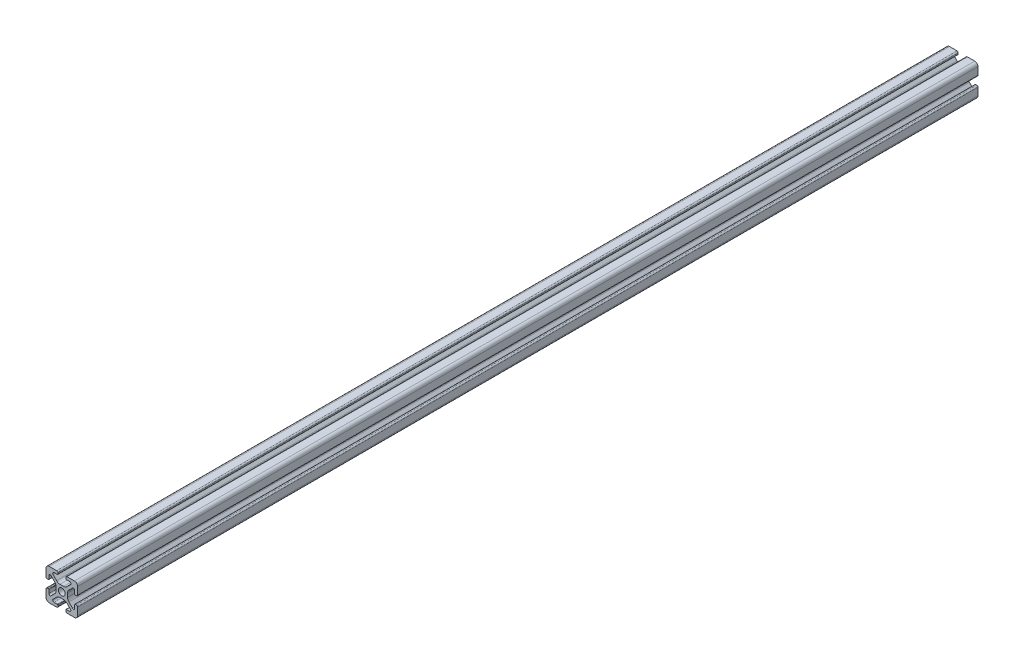
SolidWorks part; units mm, degrees
ref_plane "Front Plane" through (0, 0, 0) normal (0, 0, 1) x (1, 0, 0)
ref_plane "Top Plane" through (0, 0, 0) normal (0, 1, 0) x (1, 0, 0)
ref_plane "Right Plane" through (0, 0, 0) normal (1, 0, 0) x (0, 0, -1)
sketch "Sketch1" plane through (0, 0, 0) normal (0, 0, 1) x (1, 0, 0)
  line L2 (-9.9949, 7.9883) -> (-9.9949, 3.2893)
  line L3 (-7.9883, 9.9949) -> (-3.2893, 9.9949)
  line L4 (-2.5019, 9.2075) -> (-2.5019, 8.4963)
  line L5 (-2.8067, 8.1915) -> (-4.9149, 8.1915)
  line L6 (-5.5076, 6.7606) -> (-3.2528, 4.5058)
  line L7 (-6.7606, 5.5076) -> (-4.5058, 3.2528)
  line L8 (-8.1915, 4.9149) -> (-8.1915, 2.8067)
  line L9 (-8.4963, 2.5019) -> (-9.2075, 2.5019)
  line L11 (-1.1334, 3.6279) -> (1.1334, 3.6279)
  line L12 (-3.6279, 1.1334) -> (-3.6279, -1.1334)
  line L13 (8.4963, 2.5019) -> (9.2075, 2.5019)
  line L14 (8.1915, 4.9149) -> (8.1915, 2.8067)
  line L15 (9.9949, 7.9883) -> (9.9949, 3.2893)
  line L16 (7.9883, 9.9949) -> (3.2893, 9.9949)
  line L17 (2.5019, 9.2075) -> (2.5019, 8.4963)
  line L18 (2.8067, 8.1915) -> (4.9149, 8.1915)
  line L19 (3.6279, 1.1334) -> (3.6279, -1.1334)
  line L20 (5.5076, 6.7606) -> (3.2528, 4.5058)
  line L21 (6.7606, 5.5076) -> (4.5058, 3.2528)
  line L22 (-8.4963, -2.5019) -> (-9.2075, -2.5019)
  line L23 (-8.1915, -4.9149) -> (-8.1915, -2.8067)
  line L24 (-6.7606, -5.5076) -> (-4.5058, -3.2528)
  line L25 (-5.5076, -6.7606) -> (-3.2528, -4.5058)
  line L26 (-2.8067, -8.1915) -> (-4.9149, -8.1915)
  line L27 (-2.5019, -9.2075) -> (-2.5019, -8.4963)
  line L28 (-7.9883, -9.9949) -> (-3.2893, -9.9949)
  line L29 (-9.9949, -7.9883) -> (-9.9949, -3.2893)
  line L30 (9.9949, -7.9883) -> (9.9949, -3.2893)
  line L31 (7.9883, -9.9949) -> (3.2893, -9.9949)
  line L32 (2.5019, -9.2075) -> (2.5019, -8.4963)
  line L33 (2.8067, -8.1915) -> (4.9149, -8.1915)
  line L34 (5.5076, -6.7606) -> (3.2528, -4.5058)
  line L35 (6.7606, -5.5076) -> (4.5058, -3.2528)
  line L36 (8.1915, -4.9149) -> (8.1915, -2.8067)
  line L37 (8.4963, -2.5019) -> (9.2075, -2.5019)
  line L38 (-1.1334, -3.6279) -> (1.1334, -3.6279)
  circle A0 centre (0, 0) radius 2.1463
  arc A1 (-9.9949, 7.9883) -> (-7.9883, 9.9949) centre (-7.9883, 7.9883) cw
  arc A2 (-6.7606, 5.5076) -> (-8.1915, 4.9149) centre (-7.3533, 4.9149) ccw
  arc A3 (-4.9149, 8.1915) -> (-5.5076, 6.7606) centre (-4.9149, 7.3533) ccw
  arc A4 (-3.2893, 9.9949) -> (-2.5019, 9.2075) centre (-3.2893, 9.2075) cw
  arc A5 (-9.9949, 3.2893) -> (-9.2075, 2.5019) centre (-9.2075, 3.2893) ccw
  arc A6 (-8.1915, 2.8067) -> (-8.4963, 2.5019) centre (-8.4963, 2.8067) cw
  arc A7 (-2.5019, 8.4963) -> (-2.8067, 8.1915) centre (-2.8067, 8.4963) cw
  arc A8 (-1.1334, 3.6279) -> (-3.2528, 4.5058) centre (-1.1334, 6.6251) cw
  arc A9 (-3.6279, 1.1334) -> (-4.5058, 3.2528) centre (-6.6251, 1.1334) ccw
  arc A10 (8.1915, 2.8067) -> (8.4963, 2.5019) centre (8.4963, 2.8067) ccw
  arc A11 (9.9949, 3.2893) -> (9.2075, 2.5019) centre (9.2075, 3.2893) cw
  arc A12 (9.9949, 7.9883) -> (7.9883, 9.9949) centre (7.9883, 7.9883) ccw
  arc A13 (3.2893, 9.9949) -> (2.5019, 9.2075) centre (3.2893, 9.2075) ccw
  arc A14 (2.5019, 8.4963) -> (2.8067, 8.1915) centre (2.8067, 8.4963) ccw
  arc A15 (1.1334, 3.6279) -> (3.2528, 4.5058) centre (1.1334, 6.6251) ccw
  arc A16 (3.6279, 1.1334) -> (4.5058, 3.2528) centre (6.6251, 1.1334) cw
  arc A17 (6.7606, 5.5076) -> (8.1915, 4.9149) centre (7.3533, 4.9149) cw
  arc A18 (4.9149, 8.1915) -> (5.5076, 6.7606) centre (4.9149, 7.3533) cw
  arc A19 (-3.6279, -1.1334) -> (-4.5058, -3.2528) centre (-6.6251, -1.1334) cw
  arc A20 (-1.1334, -3.6279) -> (-3.2528, -4.5058) centre (-1.1334, -6.6251) ccw
  arc A21 (-2.5019, -8.4963) -> (-2.8067, -8.1915) centre (-2.8067, -8.4963) ccw
  arc A22 (-8.1915, -2.8067) -> (-8.4963, -2.5019) centre (-8.4963, -2.8067) ccw
  arc A23 (-9.9949, -3.2893) -> (-9.2075, -2.5019) centre (-9.2075, -3.2893) cw
  arc A24 (-3.2893, -9.9949) -> (-2.5019, -9.2075) centre (-3.2893, -9.2075) ccw
  arc A25 (-4.9149, -8.1915) -> (-5.5076, -6.7606) centre (-4.9149, -7.3533) cw
  arc A26 (-6.7606, -5.5076) -> (-8.1915, -4.9149) centre (-7.3533, -4.9149) cw
  arc A27 (-9.9949, -7.9883) -> (-7.9883, -9.9949) centre (-7.9883, -7.9883) ccw
  arc A28 (9.9949, -7.9883) -> (7.9883, -9.9949) centre (7.9883, -7.9883) cw
  arc A29 (6.7606, -5.5076) -> (8.1915, -4.9149) centre (7.3533, -4.9149) ccw
  arc A30 (4.9149, -8.1915) -> (5.5076, -6.7606) centre (4.9149, -7.3533) ccw
  arc A31 (3.2893, -9.9949) -> (2.5019, -9.2075) centre (3.2893, -9.2075) cw
  arc A32 (9.9949, -3.2893) -> (9.2075, -2.5019) centre (9.2075, -3.2893) ccw
  arc A33 (8.1915, -2.8067) -> (8.4963, -2.5019) centre (8.4963, -2.8067) cw
  arc A34 (2.5019, -8.4963) -> (2.8067, -8.1915) centre (2.8067, -8.4963) cw
  arc A35 (1.1334, -3.6279) -> (3.2528, -4.5058) centre (1.1334, -6.6251) cw
  arc A36 (3.6279, -1.1334) -> (4.5058, -3.2528) centre (6.6251, -1.1334) ccw
extrude "Boss-Extrude1" add sketch "Sketch1" along normal mid plane 569.6204
